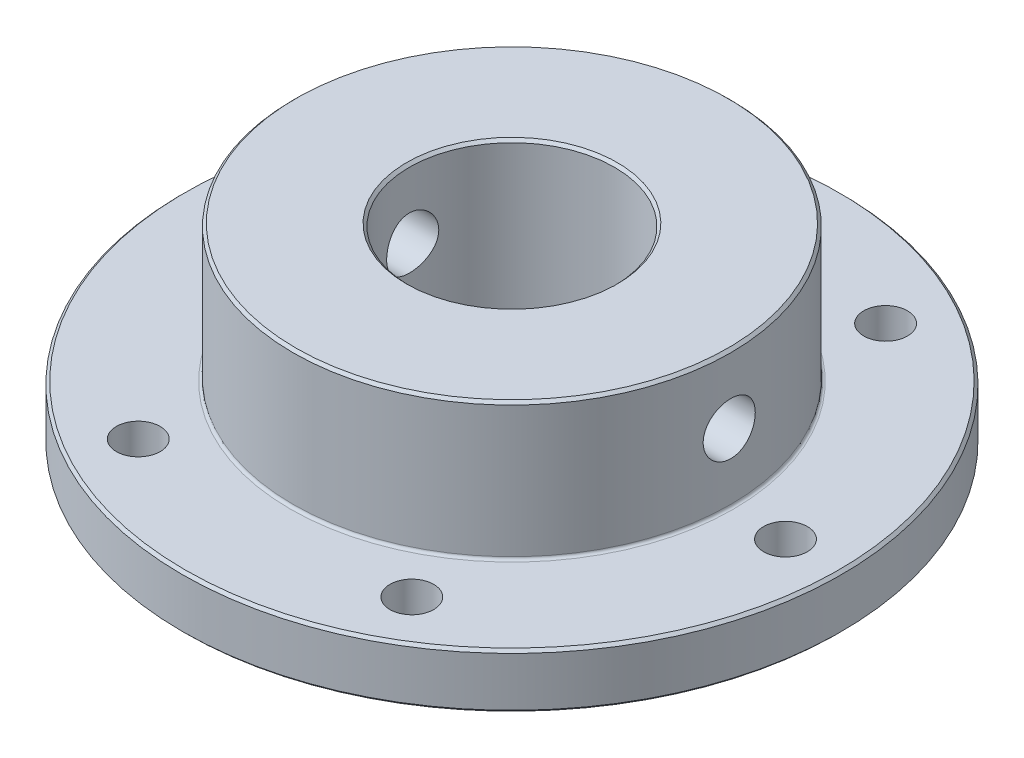
SolidWorks part; units mm, degrees
material "AISI 304"
ref_plane "Alzado" through (0, 0, 0) normal (0, 0, 1) x (1, 0, 0)
ref_plane "Planta" through (0, 0, 0) normal (0, 1, 0) x (1, 0, 0)
ref_plane "Vista lateral" through (0, 0, 0) normal (1, 0, 0) x (0, 0, -1)
sketch "Croquis1" plane through (0, 0, 0) normal (0, 1, 0) x (1, 0, 0)
  line L0 (0, 0) -> (25, -43.3013) construction
  line L1 (50, 0) -> (25, 43.3013) construction
  line L2 (25, 43.3013) -> (-25, 43.3013) construction
  line L3 (-25, 43.3013) -> (-50, 0) construction
  line L4 (-50, 0) -> (-25, -43.3013) construction
  line L5 (-25, -43.3013) -> (25, -43.3013) construction
  line L6 (25, -43.3013) -> (50, 0) construction
  circle A0 centre (0, 0) radius 18.75
  circle A1 centre (0, 0) radius 60.2396
  circle A2 centre (0, 0) radius 43.3013 construction
  circle A3 centre (25, -43.3013) radius 4
  circle A4 centre (-25, -43.3013) radius 4
  circle A5 centre (-50, 0) radius 4
  circle A6 centre (-25, 43.3013) radius 4
  circle A7 centre (25, 43.3013) radius 4
  circle A8 centre (50, 0) radius 4
  dimension "D1" = 37.5
  dimension "D5" = 8
  dimension "D2" = 50
  dimension "D4" = 50
  dimension "D3" = 6
extrude "Saliente-Extruir1" add sketch "Croquis1" along normal blind 10
sketch "Croquis2" plane through (0, 10, 0) normal (0, 1, 0) x (1, 0, 0)
  circle A0 centre (0, 0) radius 18.75
  circle A1 centre (0, 0) radius 40
  dimension "D1" = 37.5
  dimension "D2" = 80
extrude "Saliente-Extruir2" add sketch "Croquis2" along normal blind 25
chamfer "Chaflán2" distance 0.5 angle 45 4 edges at (0, 10, 60.2396) (0, 0, 60.2396) (0, 35, 40) (0, 35, 18.75)
fillet "Redondeo1" radius 0.5 1 edges at (0, 10, 40)
sketch "Croquis3" plane through (0, 0, 0) normal (1, 0, 0) x (0, 0, -1)
  line L0 (0, 35) -> (0, 10) construction
  line L1 (19.25, 35) -> (-19.25, 35) construction
  line L2 (59.7396, 10) -> (-59.7396, 10) construction
  line L3 (39.5, 35) -> (-39.5, 35) construction
  circle A0 centre (0, 22.5) radius 4.7625
  dimension "D1" = 9.525
  dimension "D2" = 25
extrude "Cortar-Extruir1" cut sketch "Croquis3" against normal through all and the other way through all
